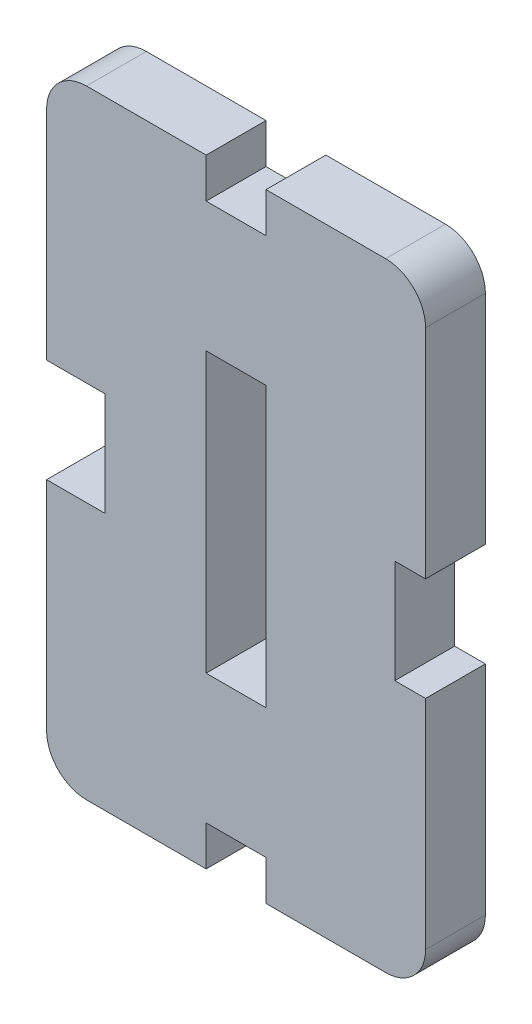
SolidWorks part; units mm, degrees
ref_plane "Front" through (0, 0, 0) normal (0, 0, 1) x (1, 0, 0)
ref_plane "Top" through (0, 0, 0) normal (0, 1, 0) x (1, 0, 0)
ref_plane "Right" through (0, 0, 0) normal (1, 0, 0) x (0, 0, -1)
sketch "Sketch1" plane through (0, 0, 0) normal (0, 0, 1) x (1, 0, 0)
  line L0 (-1044.1169, 47.4977) -> (-1044.1169, 33.4977)
  line L1 (-1049.1904, 40.4977) -> (-1034.6577, 40.4977) construction
  line L2 (-1041.1169, 33.4977) -> (-1041.1169, 47.4977)
  line L3 (-1041.1169, 47.4977) -> (-1044.1169, 47.4977)
  line L4 (-1033.1169, 53.9977) -> (-1033.1169, 43.0931)
  line L5 (-1033.1169, 43.0931) -> (-1034.6577, 43.0931)
  line L6 (-1034.6577, 43.0931) -> (-1034.6577, 37.9024)
  line L7 (-1050.1169, 24.9977) -> (-1044.1169, 24.9977)
  line L8 (-1042.6169, 53.9977) -> (-1041.1169, 53.9977)
  line L9 (-1041.1169, 53.9977) -> (-1041.1169, 55.9977)
  line L10 (-1041.1169, 55.9977) -> (-1035.1169, 55.9977)
  line L11 (-1042.6169, 53.9977) -> (-1044.1169, 53.9977)
  line L12 (-1044.1169, 53.9977) -> (-1044.1169, 55.9977)
  line L13 (-1052.1169, 37.9024) -> (-1052.1169, 26.9977)
  line L14 (-1049.1904, 37.9024) -> (-1052.1169, 37.9024)
  line L15 (-1044.1169, 26.9977) -> (-1044.1169, 24.9977)
  line L16 (-1042.6169, 26.9977) -> (-1044.1169, 26.9977)
  line L17 (-1041.1169, 24.9977) -> (-1035.1169, 24.9977)
  line L18 (-1049.1904, 37.9024) -> (-1049.1904, 43.0931)
  line L19 (-1049.1904, 43.0931) -> (-1052.1169, 43.0931)
  line L20 (-1052.1169, 43.0931) -> (-1052.1169, 53.9977)
  line L21 (-1041.1169, 26.9977) -> (-1041.1169, 24.9977)
  line L22 (-1042.6169, 26.9977) -> (-1041.1169, 26.9977)
  line L23 (-1033.1169, 37.9024) -> (-1034.6577, 37.9024)
  line L24 (-1050.1169, 55.9977) -> (-1044.1169, 55.9977)
  line L25 (-1033.1169, 26.9977) -> (-1033.1169, 37.9024)
  line L26 (-1041.1169, 33.4977) -> (-1044.1169, 33.4977)
  arc A0 (-1052.1169, 53.9977) -> (-1050.1169, 55.9977) centre (-1050.1169, 53.9977) cw
  arc A1 (-1033.1169, 53.9977) -> (-1035.1169, 55.9977) centre (-1035.1169, 53.9977) ccw
  arc A2 (-1033.1169, 26.9977) -> (-1035.1169, 24.9977) centre (-1035.1169, 26.9977) cw
  arc A3 (-1052.1169, 26.9977) -> (-1050.1169, 24.9977) centre (-1050.1169, 26.9977) ccw
  point P8 (-1044.1169, 40.4977)
  point P38 (-1041.1169, 40.4977)
  dimension "D1" = 2
  dimension "D2" = 3
  dimension "D3" = 8
  dimension "D4" = 8
  dimension "D5" = 14
  dimension "D6" = 2
  dimension "D7" = 31
extrude "Base-Extrude" add sketch "Sketch1" along normal blind 3
